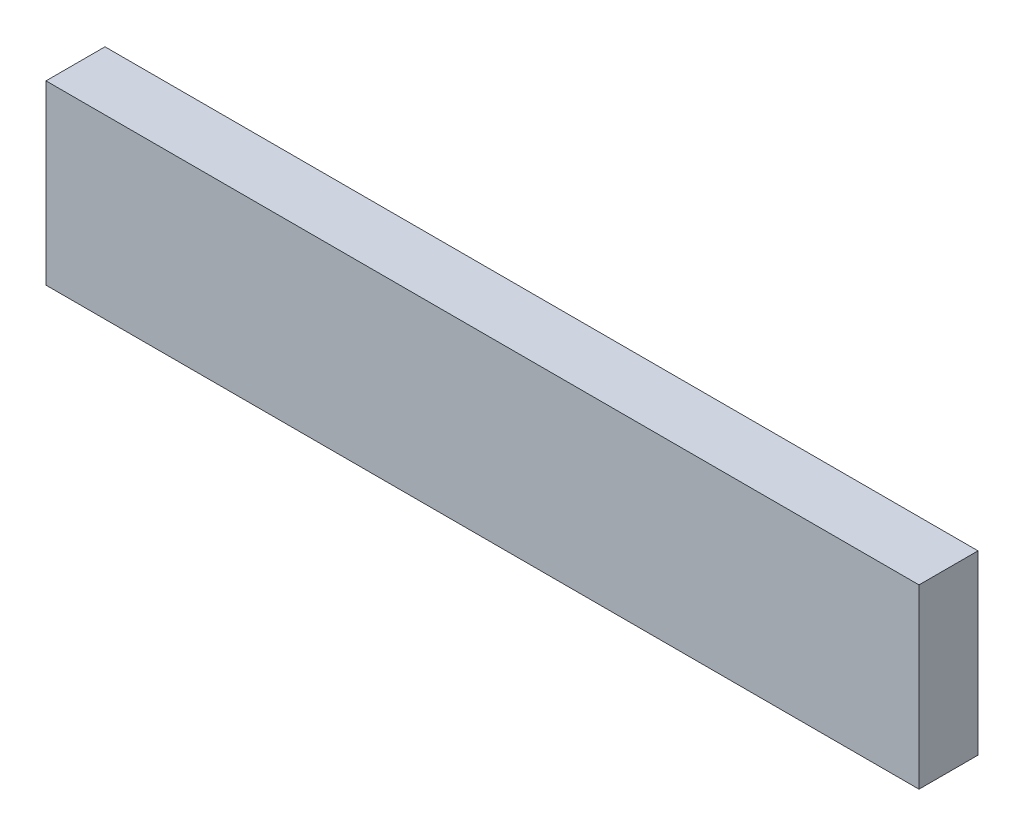
SolidWorks part; units mm, degrees
ref_plane "Front Plane" through (0, 0, 0) normal (0, 0, 1) x (1, 0, 0)
ref_plane "Top Plane" through (0, 0, 0) normal (0, 1, 0) x (1, 0, 0)
ref_plane "Right Plane" through (0, 0, 0) normal (1, 0, 0) x (0, 0, -1)
sketch "Sketch1" plane through (0, 0, 0) normal (0, 0, 1) x (1, 0, 0)
  line L1 (-37, 7.5) -> (37, 7.5)
  line L2 (-37, 7.5) -> (-37, -7.5)
  line L3 (-37, -7.5) -> (37, -7.5)
  line L4 (37, 7.5) -> (37, -7.5)
  line L5 (-37, 7.5) -> (37, -7.5) construction
  line L6 (-37, -7.5) -> (37, 7.5) construction
  point P0 (0, 0)
  dimension "D1" = 74
  dimension "D2" = 15
extrude "Boss-Extrude1" add sketch "Sketch1" along normal blind 5
